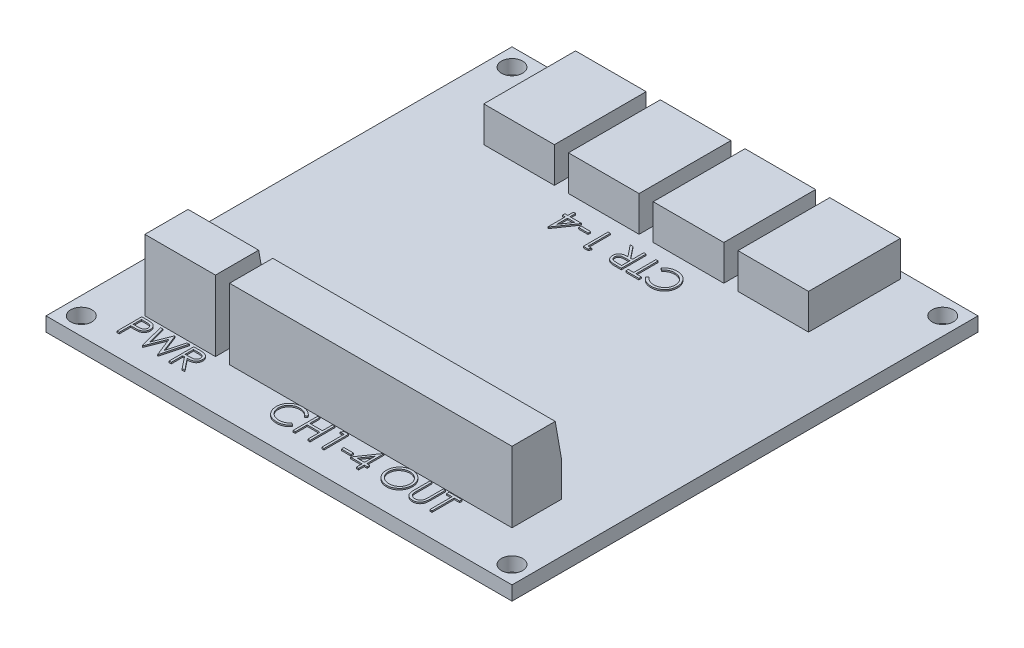
SolidWorks part; units mm, degrees
ref_plane "Ebene vorne" through (0, 0, 0) normal (0, 0, 1) x (1, 0, 0)
ref_plane "Ebene oben" through (0, 0, 0) normal (0, 1, 0) x (1, 0, 0)
ref_plane "Ebene rechts" through (0, 0, 0) normal (1, 0, 0) x (0, 0, -1)
sketch "Skizze1" plane through (0, 0, 0) normal (0, 1, 0) x (1, 0, 0)
  line L0 (0, 0) -> (0, -35974.2644) construction
  line L1 (0, 0) -> (35974.2644, 0) construction
  line L3 (-33, -33) -> (33, -33)
  line L4 (-33, -33) -> (-33, 33)
  line L5 (-33, 33) -> (33, 33)
  line L6 (33, -33) -> (33, 33)
  line L7 (-33, -33) -> (33, 33) construction
  line L8 (-33, 33) -> (33, -33) construction
  circle A0 centre (-30.5, 30.5) radius 1.5
  circle A1 centre (-30.5, -30.5) radius 1.5
  circle A2 centre (30.5, 30.5) radius 1.5
  circle A3 centre (30.5, -30.5) radius 1.5
  point P5 (0, 0)
  dimension "D3" = 2.5
  dimension "D4" = 3
  dimension "D1" = 66
  dimension "D2" = 66
extrude "Aufsatz-Linear austragen1" add sketch "Skizze1" along normal blind 2
sketch "Skizze2" plane through (0, 2, 0) normal (0, 1, 0) x (1, 0, 0)
  line L0 (-33, -26) -> (33, -26) construction
  line L1 (-33, 33) -> (-33, -33) construction
  line L2 (33, -33) -> (33, 33) construction
  line L3 (-33, -33) -> (33, -33) construction
  line L4 (-33, -19) -> (33, -19) construction
  line L6 (-14, -19) -> (26, -19)
  line L7 (-14, -19) -> (-14, -26)
  line L8 (-14, -26) -> (26, -26)
  line L9 (26, -19) -> (26, -26)
  line L10 (-16, -19) -> (-26, -19)
  line L11 (-16, -19) -> (-16, -26)
  line L12 (-16, -26) -> (-26, -26)
  line L13 (-26, -19) -> (-26, -26)
  dimension "D1" = 7
  dimension "D2" = 7
  dimension "D3" = 40
  dimension "D4" = 10
  dimension "D5" = 7
  dimension "D6" = 7
extrude "Aufsatz-Linear austragen2" add sketch "Skizze2" along normal blind 10
chamfer "Fase1" distance 5 angle 10 2 edges at (6, 12, 19) (-21, 12, 19)
sketch "Skizze3" plane through (0, 2, 0) normal (0, 1, 0) x (1, 0, 0)
  line L0 (-26.3542, -30.0278) -> (-17.4317, -30.0278) construction
  line L2 (-11.1033, -29.7743) -> (24.7628, -29.7743) construction
  text T0 "PWR"
  text T1 "CH1-4 OUT"
extrude "Aufsatz-Linear austragen3" add sketch "Skizze3" along normal blind 0.2
sketch "Skizze4" plane through (0, 2, 0) normal (0, 1, 0) x (1, 0, 0)
  line L0 (0, 33) -> (0, 8.5198) construction
  line L1 (33, 33) -> (-33, 33) construction
  line L2 (12, 33) -> (12, 10.9897) construction
  line L3 (1, 32) -> (11, 32)
  line L4 (23, 32) -> (13, 32)
  line L5 (23, 32) -> (23, 19)
  line L6 (23, 19) -> (13, 19)
  line L7 (13, 32) -> (13, 19)
  line L8 (11, 32) -> (11, 19)
  line L9 (1, 32) -> (1, 19)
  line L10 (1, 19) -> (11, 19)
  line L11 (-1, 19) -> (-11, 19)
  line L12 (-1, 32) -> (-1, 19)
  line L13 (-11, 32) -> (-11, 19)
  line L14 (-13, 32) -> (-13, 19)
  line L15 (-23, 19) -> (-13, 19)
  line L16 (-23, 32) -> (-23, 19)
  line L17 (-23, 32) -> (-13, 32)
  line L18 (-1, 32) -> (-11, 32)
  dimension "D1" = 12
  dimension "D2" = 13
  dimension "D3" = 1
  dimension "D4" = 10
  dimension "D5" = 1
extrude "Aufsatz-Linear austragen4" add sketch "Skizze4" along normal blind 5
sketch "Skizze5" plane through (0, 2, 0) normal (0, 1, 0) x (1, 0, 0)
  line L0 (23.1207, 16.8796) -> (-23.2145, 16.8796) construction
  text T0 "CTR 1-4"
extrude "Aufsatz-Linear austragen5" add sketch "Skizze5" along normal blind 0.2
